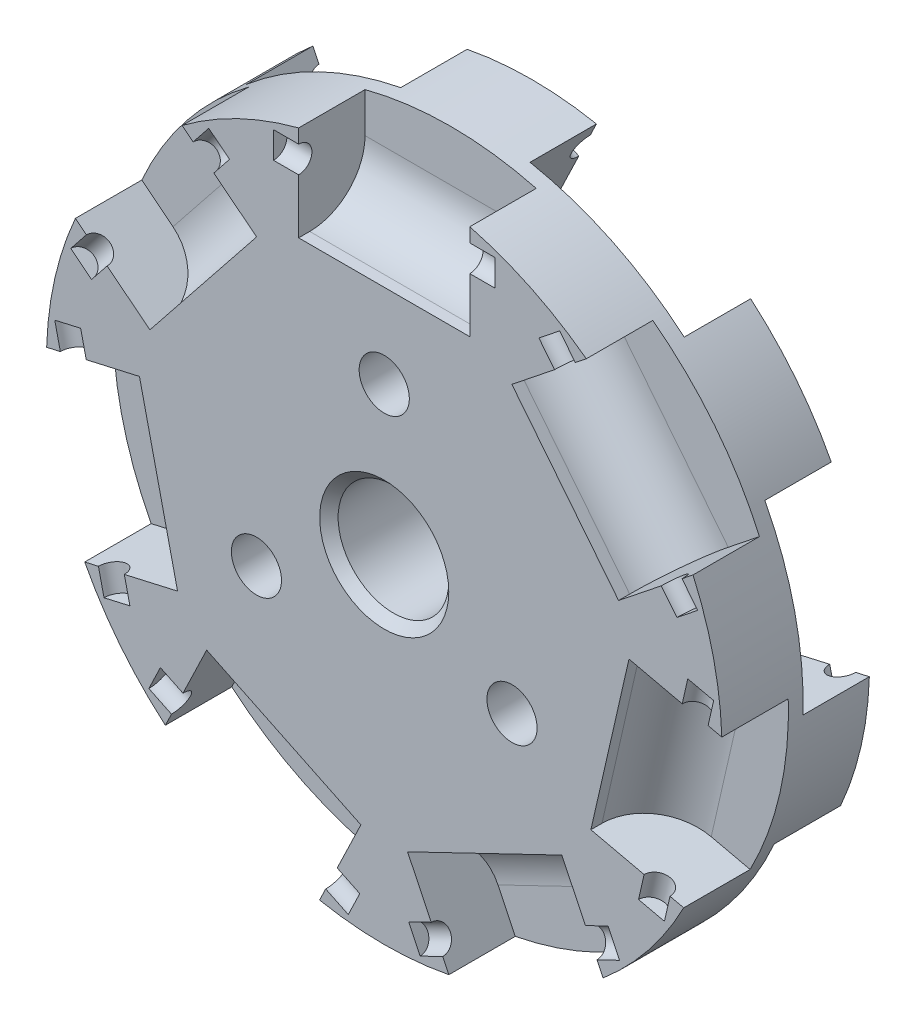
SolidWorks part; units mm, degrees
other "Markup1"
sketch "Sketch8" plane through (32.7336, 32.7336, 0) normal (0.5701, 0.1846, 0.8006) x (0.8043, 0.0736, -0.5897)
ref_plane "Front Plane" through (0, 0, 0) normal (0, 0, 1) x (1, 0, 0)
ref_plane "Top Plane" through (0, 0, 0) normal (0, 1, 0) x (1, 0, 0)
ref_plane "Right Plane" through (0, 0, 0) normal (1, 0, 0) x (0, 0, -1)
sketch "Sketch1" plane through (0, 0, 0) normal (0, 0, 1) x (1, 0, 0)
  circle A0 centre (0, 0) radius 29.0703
  dimension "D1" = 58.1406
extrude "Boss-Extrude2" add sketch "Sketch1" against normal blind 6.35
sketch "Sketch2" plane through (0, 0, 0) normal (0, 0, 1) x (1, 0, 0)
  line L1 (-12.7, 29.0703) -> (12.7, 29.0703) construction
  line L2 (-7.366, 30.3403) -> (7.366, 30.3403)
  line L3 (-7.366, 30.3403) -> (-7.366, 19.9263)
  line L4 (-7.366, 19.9263) -> (7.366, 19.9263)
  line L5 (7.366, 30.3403) -> (7.366, 19.9263)
  line L6 (-7.366, 30.3403) -> (7.366, 19.9263) construction
  line L7 (-7.366, 19.9263) -> (7.366, 30.3403) construction
  line L35 (0, 0) -> (0, 29.0703) construction
  circle A1 centre (0, 0) radius 29.0703 construction
  point P10 (0, 25.1333)
  circle M7 centre (0, 0) radius 29.0703
  dimension "D1" = 14.732
  dimension "D2" = 10.414
  dimension "D3" = 1.27
  dimension "D4" = 25.4
extrude "Cut-Extrude2" cut sketch "Sketch2" against normal blind 5.715 contours L5 L3 L4 M7
pattern_circular "CirPattern1" count 7 over 360 about axis through (0, 0, 0) along (0, 0, 1) of "Cut-Extrude2"
ref_plane "Plane1" through (0, 0, 0) normal (1, 0, 0) x (0, 0, -1)
sketch "Sketch4" plane through (0, 0, 0) normal (1, 0, 0) x (0, 0, -1)
  line L0 (5.715, 19.9263) -> (0, 19.9263) construction
  circle A0 centre (0, 25.7683) radius 1.143
  dimension "D1" = 2.286
  dimension "D2" = 5.842
extrude "Cut-Extrude4" cut sketch "Sketch4" against normal mid plane 19.05
pattern_circular "CirPattern2" count 7 over 360 about axis through (0, 0, 0) along (0, 0, 1) of "Cut-Extrude4"
sketch "Sketch5" plane through (0, 0, 0) normal (0, 0, 1) x (1, 0, 0)
  circle A0 centre (0, 0) radius 4.7625
  dimension "D1" = 9.525
extrude "Cut-Extrude5" cut sketch "Sketch5" against normal through all
sketch "Sketch6" plane through (0, 0, -6.35) normal (0, 0, -1) x (-1, 0, 0)
  circle A4 centre (0, 12.7) radius 2.159
  circle A5 centre (10.9985, -6.35) radius 2.159
  circle A6 centre (-10.9985, -6.35) radius 2.159
  point P11 (0, 0)
  dimension "D3" = 3
  dimension "D2" = 4.318
  dimension "D1" = 12.7
extrude "Cut-Extrude7" cut sketch "Sketch6" against normal through all
sketch "Sketch9" plane through (0, 0, -6.35) normal (0, 0, -1) x (-1, 0, 0)
  circle A0 centre (0, 0) radius 29.0703
  circle A5 centre (0, 12.7) radius 2.159 construction
  circle A6 centre (0, 12.7) radius 2.159
  circle A7 centre (10.9985, -6.35) radius 2.159
  circle A8 centre (-10.9985, -6.35) radius 2.159
  circle A9 centre (0, 0) radius 29.0703 construction
  circle A11 centre (0, 0) radius 4.7625 construction
  circle A12 centre (0, 0) radius 4.7625
  point P21 (0, 0)
  dimension "D1" = 3
extrude "Boss-Extrude3" add sketch "Sketch9" along normal blind 6.35
sketch "Sketch10" plane through (0, 0, -12.7) normal (0, 0, -1) x (-1, 0, 0)
  line L0 (-25.313, 26.1915) -> (0.087, 26.1915) construction
  line L1 (-2.0091, 21.149) -> (-15.2822, 14.7571)
  line L2 (-2.0091, 21.149) -> (-6.5275, 30.5317)
  line L3 (-6.5275, 30.5317) -> (-19.8006, 24.1398)
  line L4 (-15.2822, 14.7571) -> (-19.8006, 24.1398)
  line L5 (-2.0091, 21.149) -> (-19.8006, 24.1398) construction
  line L6 (-6.5275, 30.5317) -> (-15.2822, 14.7571) construction
  line L7 (0, 0) -> (-12.613, 26.1915) construction
  line L8 (0, 0) -> (0, 40.3277) construction
  circle A2 centre (0, 0) radius 29.0703 construction
  point P8 (-10.9048, 22.6444)
  dimension "D1" = 1.27
  dimension "D2" = 14.732
  dimension "D3" = 10.414
  dimension "D4" = 25.4
  dimension "D5" = 25.714
extrude "Cut-Extrude8" cut sketch "Sketch10" against normal blind 5.715
pattern_circular "CirPattern3" count 7 over 360 about axis through (0, 0, 0) along (0, 0, 1) of "Cut-Extrude8"
ref_plane "Plane2" through (0, 0, 0) normal (-0.901, 0.4339, 0) x (0, 0, -1)
sketch "Sketch11" plane through (0, 0, 0) normal (-0.901, 0.4339, 0) x (0, 0, -1)
  line L5 (6.985, -19.9263) -> (12.7, -19.9263) construction
  line L6 (12.7, -28.1216) -> (12.7, -23.2925) construction
  circle A0 centre (12.7, -25.7683) radius 1.143
  dimension "D1" = 2.286
  dimension "D2" = 5.842
extrude "Cut-Extrude9" cut sketch "Sketch11" against normal mid plane 19.05
pattern_circular "CirPattern4" count 7 over 360 about axis through (0, 0, 0) along (0, 0, 1) of "Cut-Extrude9"
fillet "Fillet1" radius 4.7625 14 edges at (-15.579, 12.4238, -5.715) (0, 19.9263, -5.715) (8.6456, 17.953, -6.985) (-8.6458, 17.9529, -6.985) (-19.4267, 4.4339, -6.985) (-15.5789, -12.4239, -6.985) (0.0001, -19.9263, -6.985) (15.5791, -12.4238, -6.985) (19.4267, 4.4341, -6.985) (8.6457, -17.953, -5.715) (19.4267, -4.434, -5.715) (-19.4267, -4.434, -5.715) (-8.6457, -17.953, -5.715) (15.579, 12.4238, -5.715)
chamfer "Chamfer1" distance 0.7937 angle 45 2 edges at (-4.7625, 0, -12.7) (4.7625, 0, 0)
